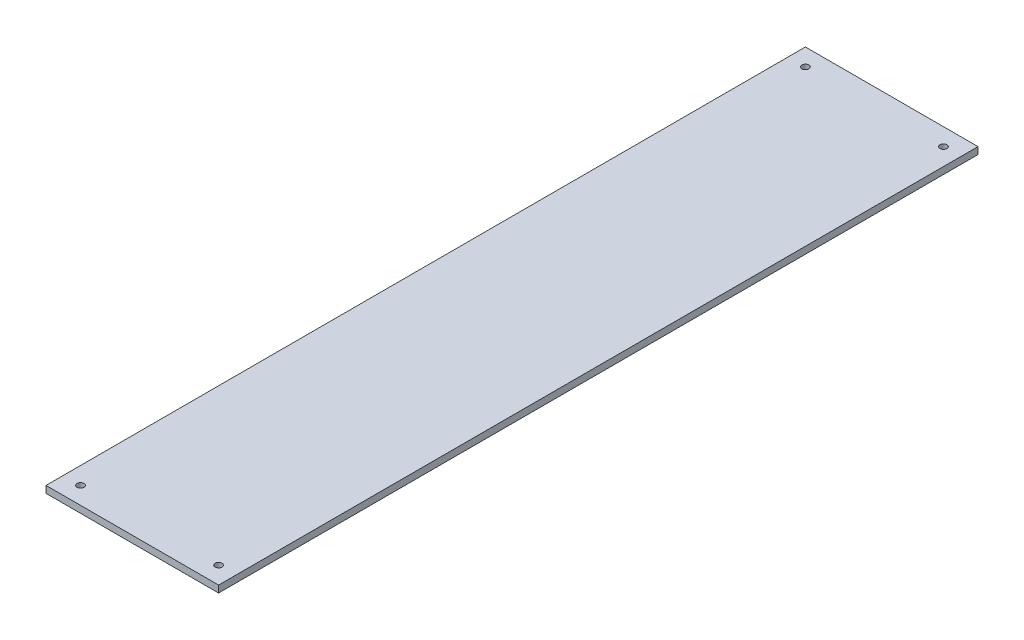
SolidWorks part; units mm, degrees
ref_plane "Front Plane" through (0, 0, 0) normal (0, 0, 1) x (1, 0, 0)
ref_plane "Top Plane" through (0, 0, 0) normal (0, 1, 0) x (1, 0, 0)
ref_plane "Right Plane" through (0, 0, 0) normal (1, 0, 0) x (0, 0, -1)
sketch "Sketch1" plane through (0, 0, 0) normal (0, 1, 0) x (1, 0, 0)
  line L1 (-125, -550) -> (125, -550)
  line L2 (-125, -550) -> (-125, 550)
  line L3 (-125, 550) -> (125, 550)
  line L4 (125, -550) -> (125, 550)
  line L5 (-125, -550) -> (125, 550) construction
  line L6 (-125, 550) -> (125, -550) construction
  point P0 (0, 0)
  dimension "D1" = 250
  dimension "D2" = 1100
extrude "Boss-Extrude1" add sketch "Sketch1" along normal blind 10
sketch "Sketch2" plane through (0, 10, 0) normal (0, 1, 0) x (1, 0, 0)
  line L0 (125, 525) -> (100, 525) construction
  line L1 (125, -550) -> (125, 550) construction
  line L2 (100, 525) -> (100, 550) construction
  line L3 (125, 550) -> (-125, 550) construction
  line L4 (-100, 550) -> (-100, 525) construction
  line L5 (-100, 525) -> (-125, 525) construction
  line L6 (-125, 550) -> (-125, -550) construction
  line L7 (125, -525) -> (100, -525) construction
  line L8 (100, -525) -> (100, -550) construction
  line L9 (-125, -550) -> (125, -550) construction
  line L10 (-100, -550) -> (-100, -525) construction
  line L11 (-100, -525) -> (-125, -525) construction
  circle A0 centre (100, 525) radius 5
  circle A1 centre (-100, 525) radius 5
  circle A2 centre (100, -525) radius 5
  circle A3 centre (-100, -525) radius 5
  dimension "D1" = 10
  dimension "D2" = 25
extrude "Cut-Extrude1" cut sketch "Sketch2" against normal through all
